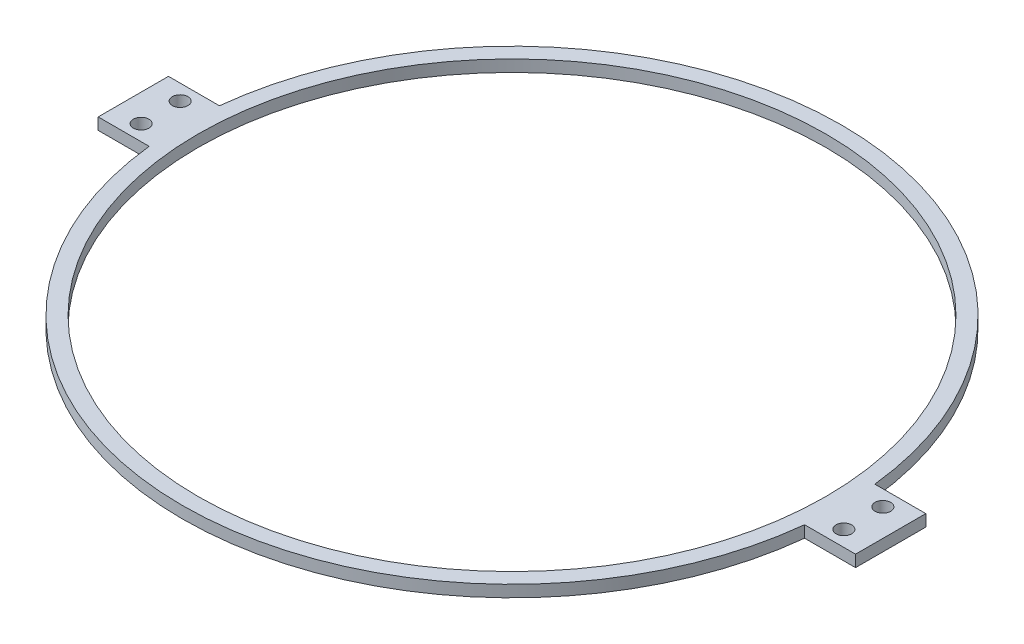
SolidWorks part; units mm, degrees
material "PLA (general purpose)"
ref_plane "Alzado" through (0, 0, 0) normal (0, 0, 1) x (1, 0, 0)
ref_plane "Planta" through (0, 0, 0) normal (0, 1, 0) x (1, 0, 0)
ref_plane "Vista lateral" through (0, 0, 0) normal (1, 0, 0) x (0, 0, -1)
sketch "Croquis1" plane through (0, 0, 0) normal (0, 1, 0) x (1, 0, 0)
  line L0 (-100, 0) -> (100, 0) construction
  line L1 (0, 100) -> (0, -100) construction
  line L2 (97, -9) -> (83.9389, -9)
  line L3 (-97, -9) -> (-83.9389, -9)
  line L4 (-97, -9) -> (-97, 9)
  line L5 (-97, 9) -> (-83.9389, 9)
  line L7 (-97, -9) -> (-83, 9) construction
  line L8 (-97, 9) -> (-83, -9) construction
  line L9 (97, 9) -> (83.9389, 9)
  line L10 (97, -9) -> (97, 9)
  circle A0 centre (0, 0) radius 80.42
  circle A1 centre (0, 0) radius 84.42
  circle A2 centre (-90, 5) radius 2
  circle A3 centre (-90, -5) radius 2
  circle A4 centre (90, 5) radius 2
  circle A5 centre (90, -5) radius 2
  point P6 (0, 0)
  point P9 (0, 0)
  point P14 (-90, 0)
  dimension "D1" = 160.84
  dimension "D2" = 168.84
  dimension "D5" = 4
  dimension "D6" = 4
  dimension "D3" = 200
  dimension "D4" = 200
  dimension "D7" = 10
  dimension "D8" = 5
  dimension "D9" = 90
  dimension "D10" = 90
  dimension "D11" = 14
  dimension "D12" = 9
  dimension "D13" = 18
  dimension "D14" = 7
  dimension "D15" = 97
extrude "Saliente-Extruir1" add sketch "Croquis1" along normal blind 3 contours A1 L2 L10 L9 A4 A5 | A1 A0 | A1 L5 L4 L3 A3 A2
sketch "Croquis2" plane through (0, 0, 0) normal (0, 1, 0) x (1, 0, 0)
  circle A0 centre (0, 0) radius 82.42
  circle A1 centre (0, 0) radius 80.42
  dimension "D1" = 164.84
  dimension "D2" = 160.84
